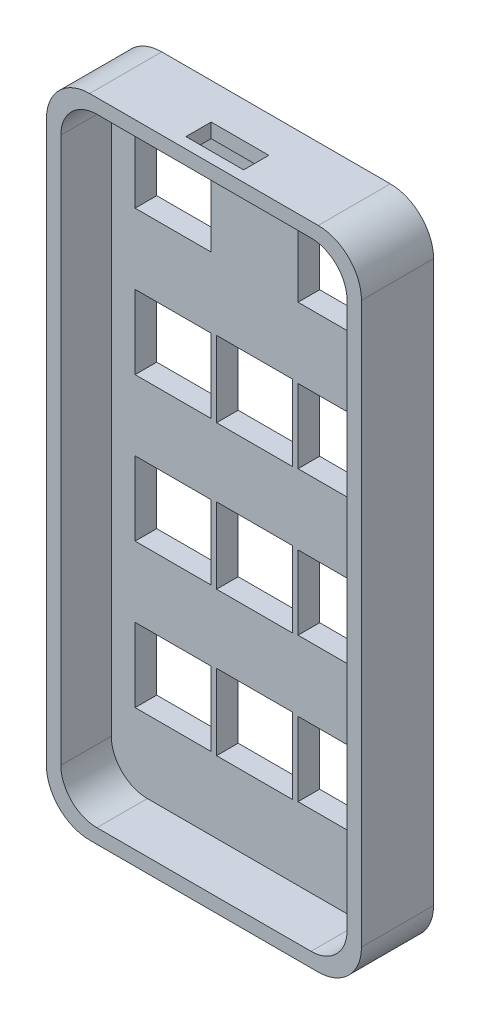
SolidWorks part; units mm, degrees
ref_plane "정면" through (0, 0, 0) normal (0, 0, 1) x (1, 0, 0)
ref_plane "윗면" through (0, 0, 0) normal (0, 1, 0) x (1, 0, 0)
ref_plane "우측면" through (0, 0, 0) normal (1, 0, 0) x (0, 0, -1)
sketch "스케치1" plane through (0, 0, 0) normal (0, 0, 1) x (1, 0, 0)
  line L1 (-19.85, -42.85) -> (19.85, -42.85)
  line L2 (-19.85, -42.85) -> (-19.85, 42.85)
  line L3 (-19.85, 42.85) -> (19.85, 42.85)
  line L4 (19.85, -42.85) -> (19.85, 42.85)
  line L5 (-19.85, -42.85) -> (19.85, 42.85) construction
  line L6 (-19.85, 42.85) -> (19.85, -42.85) construction
  point P0 (0, 0)
  dimension "D1" = 85.7
  dimension "D2" = 39.7
extrude "보스-돌출1" add sketch "스케치1" along normal blind 3
sketch "스케치3" plane through (0, 0, 0) normal (0, 0, -1) x (-1, 0, 0)
  line L0 (-19.85, 42.85) -> (19.85, 42.85) construction
  line L1 (-16.55, 27.225) -> (-6.05, 27.225)
  line L2 (-16.55, 27.225) -> (-16.55, 37.475)
  line L3 (-16.55, 37.475) -> (-6.05, 37.475)
  line L4 (-6.05, 27.225) -> (-6.05, 37.475)
  line L5 (-16.55, 27.225) -> (-6.05, 37.475) construction
  line L6 (-16.55, 37.475) -> (-6.05, 27.225) construction
  line L7 (-16.55, 7.225) -> (-16.55, 17.475)
  line L8 (-19.85, -42.85) -> (-19.85, 42.85) construction
  line L9 (0, 0) -> (0, 42.85) construction
  line L10 (0, 0) -> (19.85, 0) construction
  line L11 (19.85, 42.85) -> (19.85, -42.85) construction
  line L12 (16.55, 37.475) -> (6.05, 37.475)
  line L13 (6.05, 27.225) -> (6.05, 37.475)
  line L14 (16.55, 27.225) -> (6.05, 27.225)
  line L15 (16.55, 27.225) -> (16.55, 37.475)
  line L16 (-11.3, 32.35) -> (16.55, 32.35) construction
  line L17 (-16.55, 7.225) -> (-6.05, 7.225)
  line L18 (-5.25, 27.1) -> (5.25, 27.1)
  line L19 (-5.25, 27.1) -> (-5.25, 37.6)
  line L20 (-5.25, 37.6) -> (5.25, 37.6)
  line L21 (5.25, 27.1) -> (5.25, 37.6)
  line L22 (-5.25, 27.1) -> (5.25, 37.6) construction
  line L23 (-5.25, 37.6) -> (5.25, 27.1) construction
  line L24 (-6.05, 7.225) -> (-6.05, 17.475)
  line L25 (-16.55, 17.475) -> (-6.05, 17.475)
  line L26 (-5.25, 7.1) -> (-5.25, 17.6)
  line L27 (-5.25, 7.1) -> (5.25, 7.1)
  line L28 (5.25, 7.1) -> (5.25, 17.6)
  line L29 (-5.25, 17.6) -> (5.25, 17.6)
  line L30 (16.55, 17.475) -> (6.05, 17.475)
  line L31 (6.05, 7.225) -> (6.05, 17.475)
  line L32 (16.55, 7.225) -> (6.05, 7.225)
  line L33 (16.55, 7.225) -> (16.55, 17.475)
  line L34 (-16.55, -12.775) -> (-16.55, -2.525)
  line L35 (-16.55, -12.775) -> (-6.05, -12.775)
  line L36 (-6.05, -12.775) -> (-6.05, -2.525)
  line L37 (-16.55, -2.525) -> (-6.05, -2.525)
  line L38 (-5.25, -12.9) -> (-5.25, -2.4)
  line L39 (-5.25, -12.9) -> (5.25, -12.9)
  line L40 (5.25, -12.9) -> (5.25, -2.4)
  line L41 (-5.25, -2.4) -> (5.25, -2.4)
  line L42 (16.55, -2.525) -> (6.05, -2.525)
  line L43 (6.05, -12.775) -> (6.05, -2.525)
  line L44 (16.55, -12.775) -> (6.05, -12.775)
  line L45 (16.55, -12.775) -> (16.55, -2.525)
  line L46 (-16.55, -32.775) -> (-16.55, -22.525)
  line L47 (-16.55, -32.775) -> (-6.05, -32.775)
  line L48 (-6.05, -32.775) -> (-6.05, -22.525)
  line L49 (-16.55, -22.525) -> (-6.05, -22.525)
  line L50 (-5.25, -32.9) -> (-5.25, -22.4)
  line L51 (-5.25, -32.9) -> (5.25, -32.9)
  line L52 (5.25, -32.9) -> (5.25, -22.4)
  line L53 (-5.25, -22.4) -> (5.25, -22.4)
  line L54 (16.55, -22.525) -> (6.05, -22.525)
  line L55 (6.05, -32.775) -> (6.05, -22.525)
  line L56 (16.55, -32.775) -> (6.05, -32.775)
  line L57 (16.55, -32.775) -> (16.55, -22.525)
  point P0 (-11.3, 32.35)
  point P21 (0, 32.35)
  dimension "D1" = 10.25
  dimension "D2" = 10.5
  dimension "D3" = 10.5
  dimension "D4" = 8.55
  dimension "D5" = 10.5
  dimension "D7" = 4
extrude "컷-돌출1" cut sketch "스케치3" against normal blind 3
sketch "스케치6" plane through (0, 0, 3) normal (0, 0, 1) x (1, 0, 0)
  line L1 (-19.85, -42.85) -> (19.85, -42.85)
  line L2 (-19.85, -42.85) -> (-19.85, 42.85)
  line L3 (-19.85, 42.85) -> (19.85, 42.85)
  line L4 (19.85, -42.85) -> (19.85, 42.85)
  line L5 (-19.85, -42.85) -> (19.85, 42.85) construction
  line L6 (-19.85, 42.85) -> (19.85, -42.85) construction
  point P1 (0, 0)
extrude "돌출-얇게1" add sketch "스케치6" along normal blind 7 and the other way blind 3 thin
fillet "필렛1" radius 6 4 edges at (-21.85, 44.85, 5) (21.85, 44.85, 5) (21.85, -44.85, 5) (-21.85, -44.85, 5)
sketch "스케치7" plane through (0, 44.85, 0) normal (0, 1, 0) x (1, 0, 0)
  line L1 (-4, -8.5) -> (4, -8.5)
  line L2 (-4, -8.5) -> (-4, -5)
  line L3 (-4, -5) -> (4, -5)
  line L4 (4, -8.5) -> (4, -5)
  line L5 (-4, -8.5) -> (4, -5) construction
  line L6 (-4, -5) -> (4, -8.5) construction
  line L9 (15.85, -10) -> (-15.85, -10) construction
  point P0 (0, -6.75)
  dimension "D1" = 8
  dimension "D2" = 3.5
  dimension "D3" = 0
  dimension "D4" = 1.5
extrude "컷-돌출2" cut sketch "스케치7" against normal blind 7
fillet "필렛2" radius 5 2 edges at (-19.85, 42.85, 6.5) (19.85, 42.85, 6.5)
fillet "필렛3" radius 5 2 edges at (19.85, -42.85, 6.5) (-19.85, -42.85, 6.5)
sketch "스케치8" plane through (0, 0, 0) normal (0, 0, -1) x (-1, 0, 0)
  line L1 (-5.25, 37.6) -> (5.25, 37.6)
  line L2 (-5.25, 37.6) -> (-5.25, 27.1)
  line L3 (-5.25, 27.1) -> (5.25, 27.1)
  line L4 (5.25, 37.6) -> (5.25, 27.1)
extrude "보스-돌출2" add sketch "스케치8" against normal blind 3
sketch "스케치9" plane through (0, 0, 0) normal (0, 0, -1) x (-1, 0, 0)
  line L0 (0, 44.85) -> (0, -44.85) construction
  line L1 (-15.85, 44.85) -> (15.85, 44.85) construction
  line L2 (15.85, -44.85) -> (-15.85, -44.85) construction
  line L3 (21.85, 0) -> (-21.85, 0) construction
  line L4 (21.85, 38.85) -> (21.85, -38.85) construction
  line L5 (-21.85, -38.85) -> (-21.85, 38.85) construction
  line L6 (-18.55, 38.35) -> (18.55, 46.35) construction
  line L11 (-18.55, -1.65) -> (-18.55, 6.35)
  line L12 (5.25, 17.6) -> (-5.25, 17.6) construction
  line L13 (-18.55, 18.35) -> (18.55, 18.35)
  line L14 (-18.55, 18.35) -> (-18.55, 26.35)
  line L15 (-18.55, 26.35) -> (18.55, 26.35)
  line L16 (18.55, 18.35) -> (18.55, 26.35)
  line L17 (-18.55, 18.35) -> (18.55, 26.35) construction
  line L18 (-18.55, 26.35) -> (18.55, 18.35) construction
  line L19 (-18.55, -1.65) -> (18.55, -1.65)
  line L20 (18.55, -1.65) -> (18.55, 6.35)
  line L21 (-18.55, 6.35) -> (18.55, 6.35)
  line L22 (-18.55, -21.65) -> (-18.55, -13.65)
  line L23 (-18.55, -21.65) -> (18.55, -21.65)
  line L24 (18.55, -21.65) -> (18.55, -13.65)
  line L25 (-18.55, -13.65) -> (18.55, -13.65)
  line L26 (-18.55, -41.65) -> (-18.55, -33.65)
  line L27 (-18.55, -41.65) -> (18.55, -41.65)
  line L28 (18.55, -41.65) -> (18.55, -33.65)
  line L29 (-18.55, -33.65) -> (18.55, -33.65)
  point P12 (0, 22.35)
  dimension "D1" = 4.75
  dimension "D2" = 8
  dimension "D3" = 37.1
  dimension "D4" = 2
  dimension "D5" = 4
extrude "컷-돌출3" cut sketch "스케치9" against normal blind 0.6
